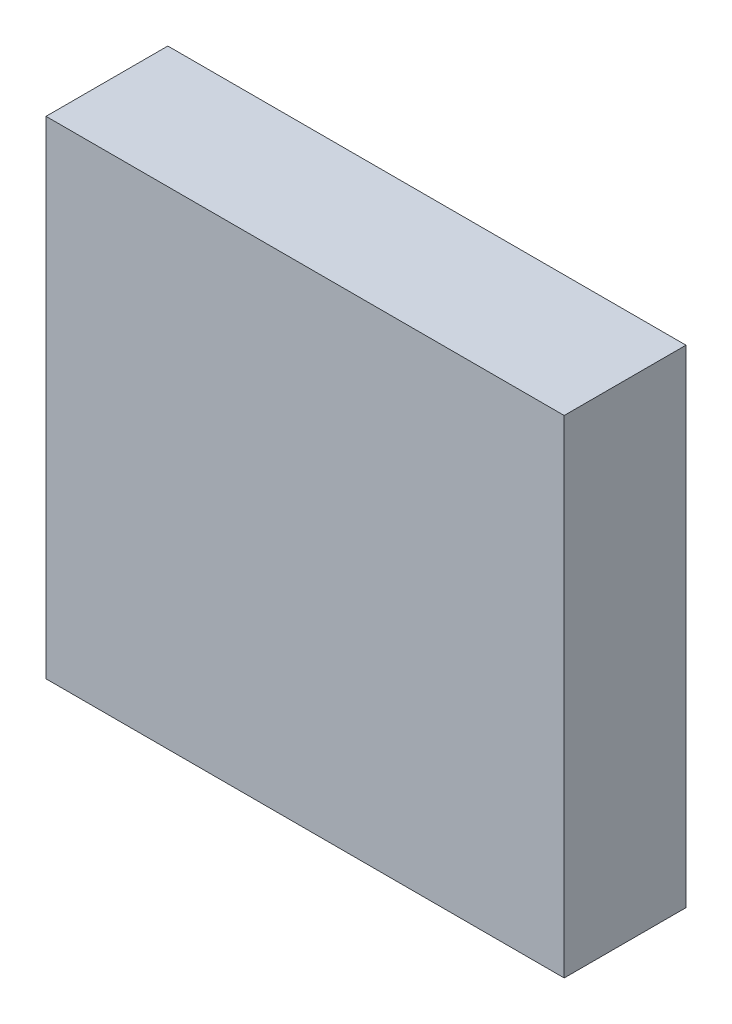
SolidWorks part; units mm, degrees
ref_plane "Front Plane" through (0, 0, 0) normal (0, 0, 1) x (1, 0, 0)
ref_plane "Top Plane" through (0, 0, 0) normal (0, 1, 0) x (1, 0, 0)
ref_plane "Right Plane" through (0, 0, 0) normal (1, 0, 0) x (0, 0, -1)
sketch "Sketch1" plane through (0, 0, 0) normal (0, 0, 1) x (1, 0, 0)
  line L1 (-53.1816, -50) -> (53.1816, -50)
  line L2 (-53.1816, -50) -> (-53.1816, 50)
  line L3 (-53.1816, 50) -> (53.1816, 50)
  line L4 (53.1816, -50) -> (53.1816, 50)
  line L5 (-53.1816, -50) -> (53.1816, 50) construction
  line L6 (-53.1816, 50) -> (53.1816, -50) construction
  point P0 (53.1816, 50)
  point P5 (0, 0)
extrude "Boss-Extrude1" add sketch "Sketch1" along normal blind 25
